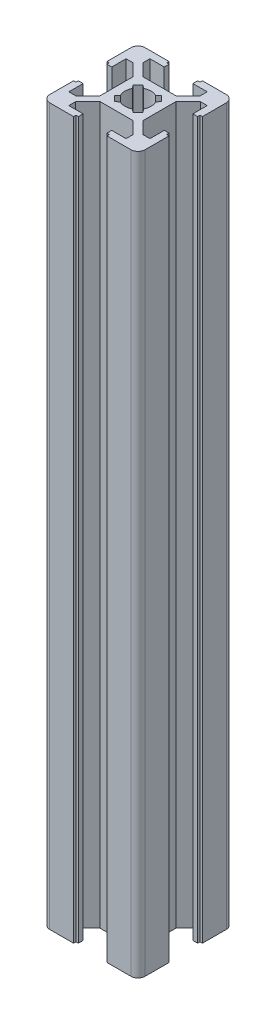
SolidWorks part; units mm, degrees
material "3.3547 (EN-AW 5083)"
ref_plane "Płaszczyzna przednia" through (0, 0, 0) normal (0, 0, 1) x (1, 0, 0)
ref_plane "Płaszczyzna górna" through (0, 0, 0) normal (0, 1, 0) x (1, 0, 0)
ref_plane "Płaszczyzna prawa" through (0, 0, 0) normal (1, 0, 0) x (0, 0, -1)
sketch "Szkic1" plane through (0, 0, 0) normal (0, 1, 0) x (1, 0, 0)
  line L0 (0, 10) -> (0, -10) construction
  line L1 (4.5, -4.5) -> (-4.5, -4.5)
  line L2 (4.5, -4.5) -> (4.5, 4.5)
  line L3 (4.5, 4.5) -> (-4.5, 4.5)
  line L4 (-4.5, -4.5) -> (-4.5, 4.5)
  line L5 (4.5, -4.5) -> (-4.5, 4.5) construction
  line L6 (4.5, 4.5) -> (-4.5, -4.5) construction
  line L7 (8.5, -10) -> (-8.5, -10)
  line L8 (10, -8.5) -> (10, 8.5)
  line L9 (8.5, 10) -> (-8.5, 10)
  line L10 (-10, -8.5) -> (-10, 8.5)
  line L11 (10, -10) -> (-10, 10) construction
  line L12 (10, 10) -> (-10, -10) construction
  line L13 (3.5, 10) -> (-3.5, 10)
  line L14 (-3.5, 10) -> (-3.5, 9.5)
  line L15 (-3.5, 9.5) -> (-3, 9.5)
  line L16 (-3, 9.5) -> (-3, 8.5)
  line L17 (-3, 8.5) -> (-6, 8.5)
  line L18 (-6, 8.5) -> (-6, 7.06)
  line L19 (-6, 7.06) -> (-3.4405, 4.5)
  line L20 (-1.9445, 3.0052) -> (-3.0052, 1.9445)
  line L21 (-1.9445, 3.0052) -> (-1.2713, 2.4385)
  line L22 (-3.0052, 1.9445) -> (-2.4385, 1.2713)
  line L23 (3.5, 10) -> (3.5, 9.5)
  line L24 (3.5, 9.5) -> (3, 9.5)
  line L25 (3, 9.5) -> (3, 8.5)
  line L26 (3, 8.5) -> (6, 8.5)
  line L27 (6, 8.5) -> (6, 7.06)
  line L28 (6, 7.06) -> (3.4405, 4.5)
  line L29 (1.9445, 3.0052) -> (3.0052, 1.9445)
  line L30 (1.9445, 3.0052) -> (1.2713, 2.4385)
  line L31 (3.0052, 1.9445) -> (2.4385, 1.2713)
  line L32 (1.9445, 3.0052) -> (1.2713, 2.4385)
  line L33 (3.0052, 1.9445) -> (1.9445, 3.0052)
  line L34 (3.0052, 1.9445) -> (2.4385, 1.2713)
  line L35 (7.06, 6) -> (4.5, 3.4405)
  line L36 (8.5, 6) -> (7.06, 6)
  line L37 (8.5, 3) -> (8.5, 6)
  line L38 (9.5, 3) -> (8.5, 3)
  line L39 (9.5, 3.5) -> (9.5, 3)
  line L40 (10, 3.5) -> (9.5, 3.5)
  line L41 (10, -3.5) -> (9.5, -3.5)
  line L42 (9.5, -3.5) -> (9.5, -3)
  line L43 (9.5, -3) -> (8.5, -3)
  line L44 (8.5, -3) -> (8.5, -6)
  line L45 (8.5, -6) -> (7.06, -6)
  line L46 (7.06, -6) -> (4.5, -3.4405)
  line L47 (3.0052, -1.9445) -> (2.4385, -1.2713)
  line L48 (3.0052, -1.9445) -> (1.9445, -3.0052)
  line L49 (1.9445, -3.0052) -> (1.2713, -2.4385)
  line L50 (3.0052, -1.9445) -> (2.4385, -1.2713)
  line L51 (1.9445, -3.0052) -> (3.0052, -1.9445)
  line L52 (1.9445, -3.0052) -> (1.2713, -2.4385)
  line L53 (6, -7.06) -> (3.4405, -4.5)
  line L54 (6, -8.5) -> (6, -7.06)
  line L55 (3, -8.5) -> (6, -8.5)
  line L56 (3, -9.5) -> (3, -8.5)
  line L57 (3.5, -9.5) -> (3, -9.5)
  line L58 (3.5, -10) -> (3.5, -9.5)
  line L59 (-3.5, -10) -> (-3.5, -9.5)
  line L60 (-3.5, -9.5) -> (-3, -9.5)
  line L61 (-3, -9.5) -> (-3, -8.5)
  line L62 (-3, -8.5) -> (-6, -8.5)
  line L63 (-6, -8.5) -> (-6, -7.06)
  line L64 (-6, -7.06) -> (-3.4405, -4.5)
  line L65 (-1.9445, -3.0052) -> (-1.2713, -2.4385)
  line L66 (-1.9445, -3.0052) -> (-3.0052, -1.9445)
  line L67 (-3.0052, -1.9445) -> (-2.4385, -1.2713)
  line L68 (-1.9445, -3.0052) -> (-1.2713, -2.4385)
  line L69 (-3.0052, -1.9445) -> (-1.9445, -3.0052)
  line L70 (-3.0052, -1.9445) -> (-2.4385, -1.2713)
  line L71 (-7.06, -6) -> (-4.5, -3.4405)
  line L72 (-8.5, -6) -> (-7.06, -6)
  line L73 (-8.5, -3) -> (-8.5, -6)
  line L74 (-9.5, -3) -> (-8.5, -3)
  line L75 (-9.5, -3.5) -> (-9.5, -3)
  line L76 (-10, -3.5) -> (-9.5, -3.5)
  line L77 (-10, 3.5) -> (-9.5, 3.5)
  line L78 (-9.5, 3.5) -> (-9.5, 3)
  line L79 (-9.5, 3) -> (-8.5, 3)
  line L80 (-8.5, 3) -> (-8.5, 6)
  line L81 (-8.5, 6) -> (-7.06, 6)
  line L82 (-7.06, 6) -> (-4.5, 3.4405)
  line L83 (-3.0052, 1.9445) -> (-2.4385, 1.2713)
  line L84 (-3.0052, 1.9445) -> (-1.9445, 3.0052)
  line L85 (-1.9445, 3.0052) -> (-1.2713, 2.4385)
  circle A0 centre (0, 0) radius 2.75
  arc A1 (10, -8.5) -> (8.5, -10) centre (8.5, -8.5) cw
  arc A2 (-10, -8.5) -> (-8.5, -10) centre (-8.5, -8.5) ccw
  arc A3 (10, 8.5) -> (8.5, 10) centre (8.5, 8.5) ccw
  arc A4 (-8.5, 10) -> (-10, 8.5) centre (-8.5, 8.5) ccw
  point P16 (0, 10)
  point P37 (-2.4749, 2.4749)
  dimension "D1" = 5.5
  dimension "D12" = 1.5
  dimension "D2" = 9
  dimension "D3" = 20
  dimension "D4" = 20
  dimension "D5" = 7
  dimension "D6" = 0.5
  dimension "D7" = 0.5
  dimension "D8" = 1
  dimension "D9" = 3
  dimension "D10" = 1.44
  dimension "D11" = 3.62
  dimension "D13" = 1.5
  dimension "D14" = 3.5
  dimension "D15" = 0.88
  dimension "D16" = 4
extrude "Dodanie-wyciągnięcie1" add sketch "Szkic1" along normal blind 150 contours L9 A4 L10 L77 L78 L79 L80 L81 L82 L4 L3 L19 L18 L17 L16 L15 L14 | L8 A3 L9 L23 L24 L25 L26 L27 L28 L3 L2 L35 L36 L37 L38 L39 L40 | L4 L1 L2 L3 A0 L47 L48 L49 L65 L66 L67 L22 L20 L21 L30 L29 L31 | L10 A2 L7 L59 L60 L61 L62 L63 L64 L1 L4 L71 L72 L73 L74 L75 L76 | A1 L8 L41 L42 L43 L44 L45 L46 L2 L1 L53 L54 L55 L56 L57 L58 L7
ref_plane "Plane1" through (0, 75, 0) normal (0, 1, 0) x (1, 0, 0)
